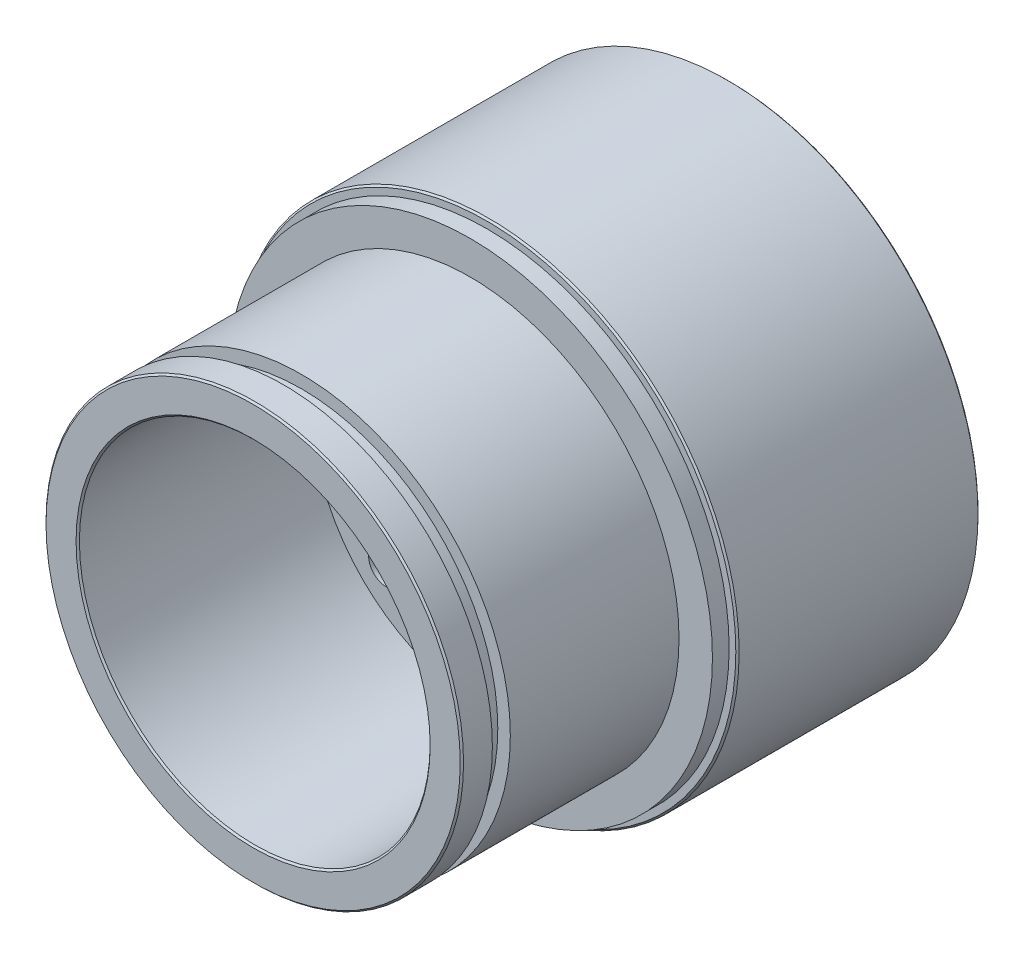
SolidWorks part; units mm, degrees
material "1060 Alloy"
ref_plane "Front Plane" through (0, 0, 0) normal (0, 0, 1) x (1, 0, 0)
ref_plane "Top Plane" through (0, 0, 0) normal (0, 1, 0) x (1, 0, 0)
ref_plane "Right Plane" through (0, 0, 0) normal (1, 0, 0) x (0, 0, -1)
sketch "Sketch1" plane through (0, 0, 0) normal (0, 1, 0) x (1, 0, 0)
  line L0 (0, 0) -> (0, 29) construction
  line L1 (13, 0) -> (21, 0)
  line L2 (21, 0) -> (21, -28)
  line L3 (21, -28) -> (25, -28)
  line L4 (25, -28) -> (25, -2)
  line L5 (29, 0) -> (30, 0)
  line L6 (30, 0) -> (30, 29)
  line L9 (30, 29) -> (20.5, 29)
  line L10 (20.5, 29) -> (20.5, 4)
  line L11 (20.5, 4) -> (13, 4)
  line L12 (13, 4) -> (13, 0)
  line L13 (25, -2) -> (29, -2)
  line L14 (29, -2) -> (29, 0)
  dimension "D1" = 26
  dimension "D2" = 50
  dimension "D3" = 4
  dimension "D4" = 4
  dimension "D5" = 41
  dimension "D6" = 25
  dimension "D7" = 58
  dimension "D10" = 2
  dimension "D11" = 60
  dimension "D12" = 26
revolve "Revolve1" add sketch "Sketch1" angle 360 about L0
sketch "Sketch2" plane through (0, 0, 0) normal (0, 1, 0) x (1, 0, 0)
  line L0 (25, -28) -> (25, -2) construction
  line L1 (25, -22.2) -> (23.5, -22.2)
  line L2 (25, -22.2) -> (25, -24.35)
  line L3 (25, -24.35) -> (23.5, -24.35)
  line L4 (23.5, -22.2) -> (23.5, -24.35)
  line L5 (0, 0) -> (0, -28) construction
  line L6 (-25, 0) -> (25, 0) construction
  line L7 (-25, -28) -> (25, -28) construction
  line L9 (-29, -2) -> (29, -2) construction
  dimension "D1" = 2.15
  dimension "D2" = 47
  dimension "D3" = 20.2
revolve "Cut-Revolve1" cut sketch "Sketch2" angle 360 about L5
chamfer "Chamfer1" distance 0.2 angle 45 5 edges at (30, 0, 0) (20.5, 0, -29) (25, 0, 28) (21, 0, 28) (30, 0, -29)
hole_wizard "M4 Clearance Hole1" positions "Sketch3" profile "Sketch4" hole size "M4" standard "ISO" end condition through all
sketch "Sketch3" plane through (0, 0, 0) normal (0, 0, 1) x (1, 0, 0)
  line L0 (-12.0208, 12.0208) -> (0, 0) construction
  line L2 (0, 0) -> (0, 8.8626) construction
  point P0 (-12.0208, 12.0208)
  dimension "D1" = 17
  dimension "D2" = 45
sketch "Sketch4" plane through (-12.0208, 12.0208, 0) normal (1, 0, 0) x (0, -1, 0)
  line L0 (0, 0) -> (0, 29)
  line L1 (0, 29) -> (2.15, 29)
  line L2 (2.15, 29) -> (2.15, 0)
  line L5 (2.15, 0) -> (0, 0)
  line L11 (0, -6.35) -> (0, 107.95) construction
  dimension "Thru Hole Dia." = 4.3
  dimension "Thru Hole Depth" = 29
pattern_circular "CirPattern1" count 4 over 360 about axis through (0, 0, 0) along (0, 0, 1) of "M4 Clearance Hole1"
hole_wizard "M4 Tapped Hole1" positions "Sketch8" profile "Sketch9" tap size "M4" standard "ISO"
sketch "Sketch8" plane through (0, 0, -29) normal (0, 0, -1) x (-1, 0, 0)
  point P0 (0, 25)
  dimension "D1" = 25
cosmetic thread "Hole Thread3" parameters "D1"=8, "D2"=4
sketch "Sketch9" plane through (0, 25, -29) normal (1, 0, 0) x (0, 1, 0)
  line L0 (0, 0) -> (0, 11.0914)
  line L1 (0, 11.0914) -> (1.65, 10.1)
  line L2 (1.65, 10.1) -> (1.65, 0)
  line L5 (1.65, 0) -> (0, 0)
  line L10 (0, 11.0914) -> (-1.65, 10.1) construction
  line L11 (0, -6.35) -> (0, 107.95) construction
  dimension "Tap Drill Dia." = 3.3
  dimension "Tap Drill Depth" = 10.1
  dimension "Drill Angle" = 118
pattern_circular "CirPattern3" count 6 over 360 about axis through (0, 0, 0) along (0, 0, 1) of "M4 Tapped Hole1"
move or copy body "Body-Move/Copy1" [suppressed] bodies to move or copy 109
